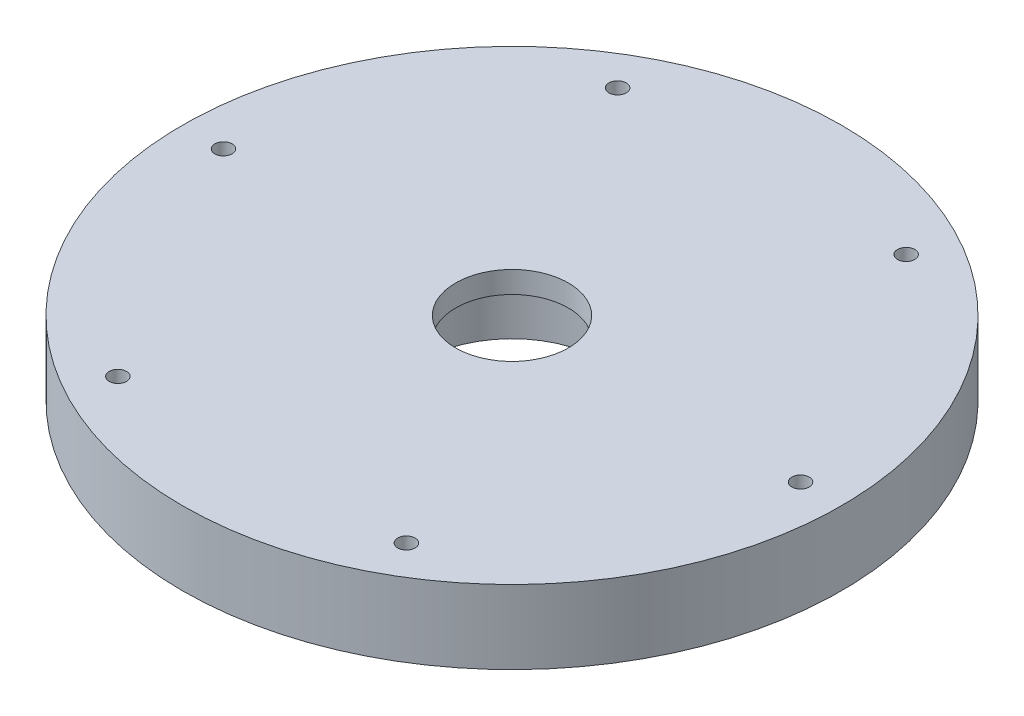
SolidWorks part; units mm, degrees
material "1060 Alloy"
ref_plane "Front Plane" through (0, 0, 0) normal (0, 0, 1) x (1, 0, 0)
ref_plane "Top Plane" through (0, 0, 0) normal (0, 1, 0) x (1, 0, 0)
ref_plane "Right Plane" through (0, 0, 0) normal (1, 0, 0) x (0, 0, -1)
sketch "Sketch1" plane through (0, 0, 0) normal (0, 0, 1) x (1, 0, 0)
  line L0 (0, 38.7087) -> (0, -19.5852) construction
  line L1 (-6.5, 0) -> (-38, 0)
  line L2 (-38, 0) -> (-38, -8.5)
  line L4 (-10.5, -9.75) -> (-10.5, -2.5)
  line L5 (-10.5, -2.5) -> (-6.5, -2.5)
  line L6 (-6.5, -2.5) -> (-6.5, 0)
  line L7 (-10.5, -9.75) -> (-35, -9.75)
  line L8 (-35, -9.75) -> (-35, -8.5)
  line L9 (-35, -8.5) -> (-38, -8.5)
  dimension "D1" = 6.5
  dimension "D2" = 10.5
  dimension "D4" = 38
  dimension "D5" = 3
  dimension "D6" = 1.25
  dimension "D7" = 2.5
  dimension "D3" = 6
revolve "Revolve1" add sketch "Sketch1" angle 360 about L0
sketch "Sketch2" plane through (0, -9.75, 0) normal (0, -1, 0) x (1, 0, 0)
  circle A0 centre (0, 0) radius 33.2687 construction
  circle A1 centre (-33.2687, 0) radius 1
  circle A2 centre (-16.6344, 28.8116) radius 1
  circle A3 centre (16.6344, 28.8116) radius 1
  circle A4 centre (33.2687, 0) radius 1
  circle A5 centre (16.6344, -28.8116) radius 1
  circle A6 centre (-16.6344, -28.8116) radius 1
  point P17 (0, 0)
  dimension "D1" = 2
  dimension "D3" = 66.5375
  dimension "D2" = 6
extrude "Cut-Extrude1" cut sketch "Sketch2" against normal through all
equation "\"Stator_OD\"= 60'No Tolerance given"
equation "\"A\"=35.81 'taken off spec sheet for 06808 (A)"
equation "\"Rotor_ID\"= 30'No Tolerance Given"
equation "\"back_bearing_Thickness\"= 5'-0.12"
equation "\"back_bearing_OD\"= 24'-0.009 https://www.mcmaster.com/5972K155/"
equation "\"Stator_Gap\"= 0.0375'+- 0.0125 (From 1.3.3.1 Kollmorgen manual)"
equation "\"Back_mount_hole\"= 1.75'To be tapped to M2 (USE LOCKTITE)"
equation "\"facePlate_Mount_Hole\"= 2.75'To be tapped to M3"
equation "\"back_bearing_ID\"= 15'"
equation "\"final_shaftD\"= 12'To fit in harmonic"
equation "\"final_shaftL\"= 50'random length. Idk"
equation "\"back_bearing_IDOD\"= 16.5'measured off CAD, actually 16.75, but rounded down to nicer number"
equation "\"rotor_shaftD\"= \"Rotor_ID\" - (\"rotor-shaft_gap\")*2'"
equation "\"front_bearing_ID\"= 12'https://www.mcmaster.com/5972K154/"
equation "\"front_bearing_OD\"= 21'-0.009"
equation "\"front_bearing_IDOD\"= 13.5'Measured off CAD. Actually 13.75, but rounded down"
equation "\"front_bearing_Thickness\"= 5'-0.12"
equation "\"rotor_thickness\"= 2.4'measured off CAD"
equation "\"rotor_height\"= 32.86'+-0.075 taken off spec sheet for 06826 (C)"
equation "\"D1@Sketch1\"=\"final_shaftD\"/2+0.5"
equation "\"D2@Sketch1\"=\"front_bearing_OD\"/2"
equation "\"D4@Sketch1\"=\"Stator_OD\"/2+8"
equation "\"D3@Sketch1\"=\"front_bearing_Thickness\"+1"
equation "\"D3@Sketch2\"=\"Stator_OD\" + \"Stator_Gap\"  + 6.5"
equation "\"D1@Sketch2\"=\"Back_mount_hole\"+0.25"
